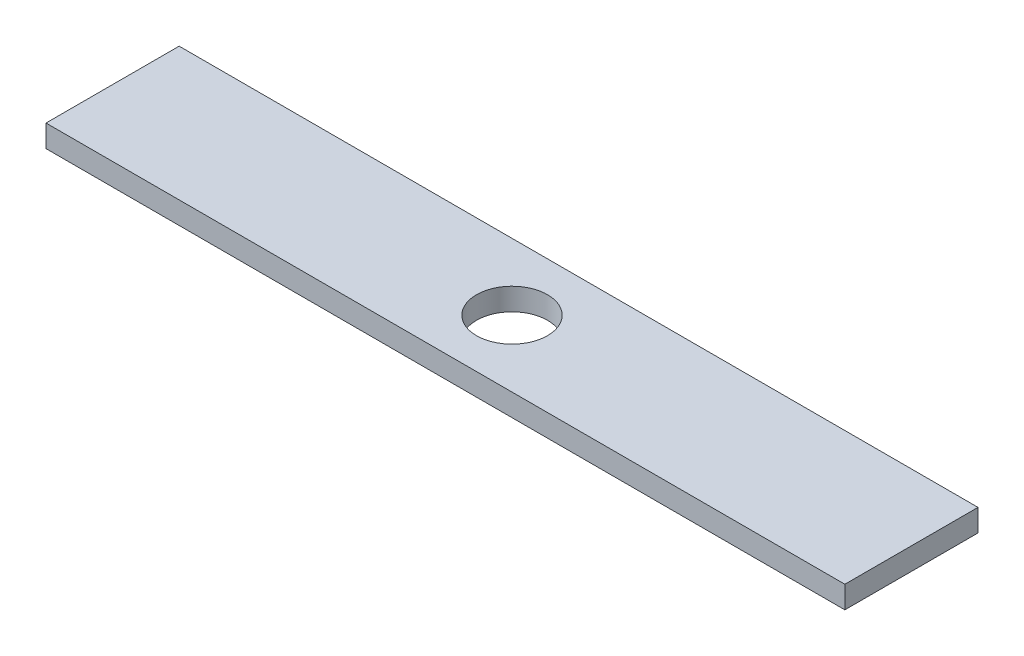
SolidWorks part; units mm, degrees
ref_plane "前视基准面" through (0, 0, 0) normal (0, 0, 1) x (1, 0, 0)
ref_plane "上视基准面" through (0, 0, 0) normal (0, 1, 0) x (1, 0, 0)
ref_plane "右视基准面" through (0, 0, 0) normal (1, 0, 0) x (0, 0, -1)
sketch "草图1" plane through (0, 0, 0) normal (0, 1, 0) x (1, 0, 0)
  line L1 (-90, -15) -> (90, -15)
  line L2 (-90, -15) -> (-90, 15)
  line L3 (-90, 15) -> (90, 15)
  line L4 (90, -15) -> (90, 15)
  line L5 (-90, -15) -> (90, 15) construction
  line L6 (-90, 15) -> (90, -15) construction
  point P0 (0, 0)
  dimension "D1" = 180
  dimension "D2" = 30
extrude "凸台-拉伸1" add sketch "草图1" along normal blind 5
sketch "草图2" plane through (0, 5, 0) normal (0, 1, 0) x (1, 0, 0)
  circle A0 centre (0, 0) radius 8
  dimension "D1" = 16
extrude "切除-拉伸1" cut sketch "草图2" against normal blind 5
